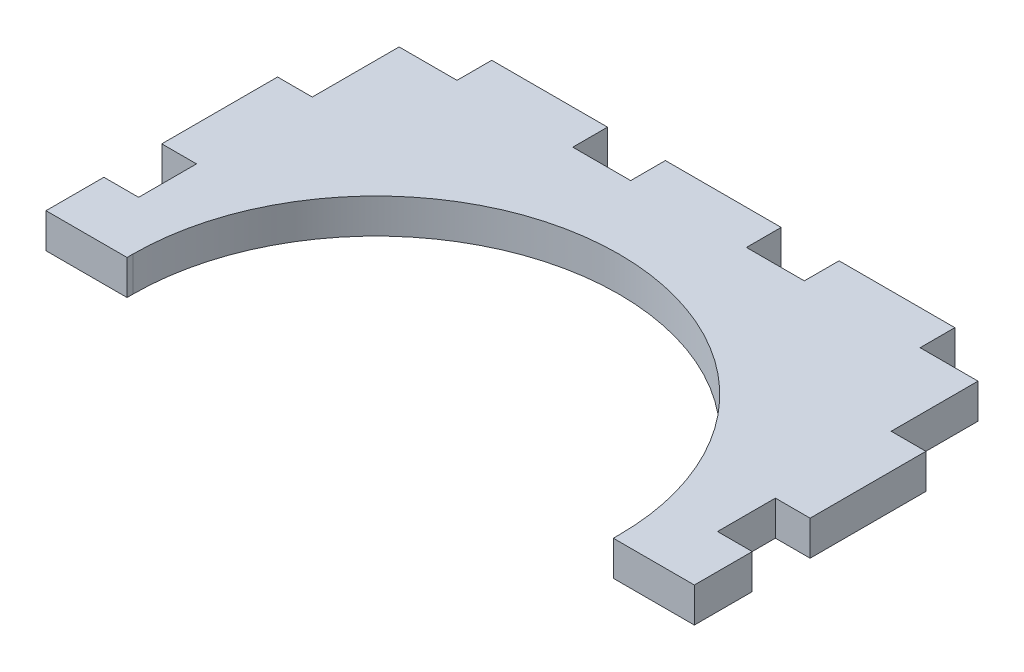
SolidWorks part; units mm, degrees
material "轻木"
ref_plane "前视基准面" through (0, 0, 0) normal (0, 0, 1) x (1, 0, 0)
ref_plane "上视基准面" through (0, 0, 0) normal (0, 1, 0) x (1, 0, 0)
ref_plane "右视基准面" through (0, 0, 0) normal (1, 0, 0) x (0, 0, -1)
sketch "草图2" plane through (0, 0, 0) normal (0, 1, 0) x (1, 0, 0)
  line L1 (-25, 27.5) -> (-20, 27.5)
  line L2 (-25, 27.5) -> (-25, 20)
  line L4 (25, 27.5) -> (25, 20)
  line L6 (0, -55) -> (0, 55) construction
  line L7 (-25, 20) -> (-28, 20)
  line L9 (-25, 10) -> (-28, 10)
  line L10 (-28, 20) -> (-28, 10)
  line L11 (-25, 5) -> (-28, 5)
  line L12 (-28, 5) -> (-28, 0.5)
  line L23 (25, 5) -> (28, 5)
  line L24 (28, 5) -> (28, 0.5)
  line L27 (25, 10) -> (28, 10)
  line L28 (28, 20) -> (28, 10)
  line L29 (25, 20) -> (28, 20)
  line L31 (-5, 27.5) -> (-5, 30.5)
  line L33 (-20, 27.5) -> (-20, 30.5)
  line L34 (-20, 30.5) -> (-10, 30.5)
  line L35 (-10, 27.5) -> (-10, 30.5)
  line L37 (5, 27.5) -> (5, 30.5)
  line L38 (-5, 30.5) -> (5, 30.5)
  line L39 (10, 27.5) -> (10, 30.5)
  line L41 (20, 27.5) -> (20, 30.5)
  line L42 (10, 30.5) -> (20, 30.5)
  line L56 (-25, 10) -> (-25, 5)
  line L64 (25, 10) -> (25, 5)
  line L65 (20, 27.5) -> (25, 27.5)
  line L67 (5, 27.5) -> (10, 27.5)
  line L69 (-10, 27.5) -> (-5, 27.5)
  line L72 (-28, 0.5) -> (-28, 0)
  line L73 (-28, -10) -> (-28, -20) [skipped]
  line L74 (-25, -10) -> (-28, -10) [skipped]
  line L75 (-25, -20) -> (-28, -20) [skipped]
  line L76 (-25, -5) -> (-28, -5) [skipped]
  line L77 (-28, 0) -> (-21, 0)
  line L78 (-21, 0) -> (-21, 0.5)
  line L79 (21, 0.5) -> (21, 0)
  line L80 (21, 0) -> (28, 0)
  line L81 (28, 0) -> (28, 0.5)
  arc A0 (21, 0.5) -> (-21, 0.5) centre (0, 0.5) ccw
  point P0 (0, 0)
  dimension "D11" = 27
  dimension "D12" = 42
  dimension "D1" = 50
  dimension "D3" = 3
  dimension "D4" = 10
  dimension "D5" = 7.5
  dimension "D7" = 3
  dimension "D8" = 10
  dimension "D9" = 5
  dimension "D6" = 3
  dimension "D10" = 3
extrude "凸台-拉伸1" add sketch "草图2" along normal blind 3
